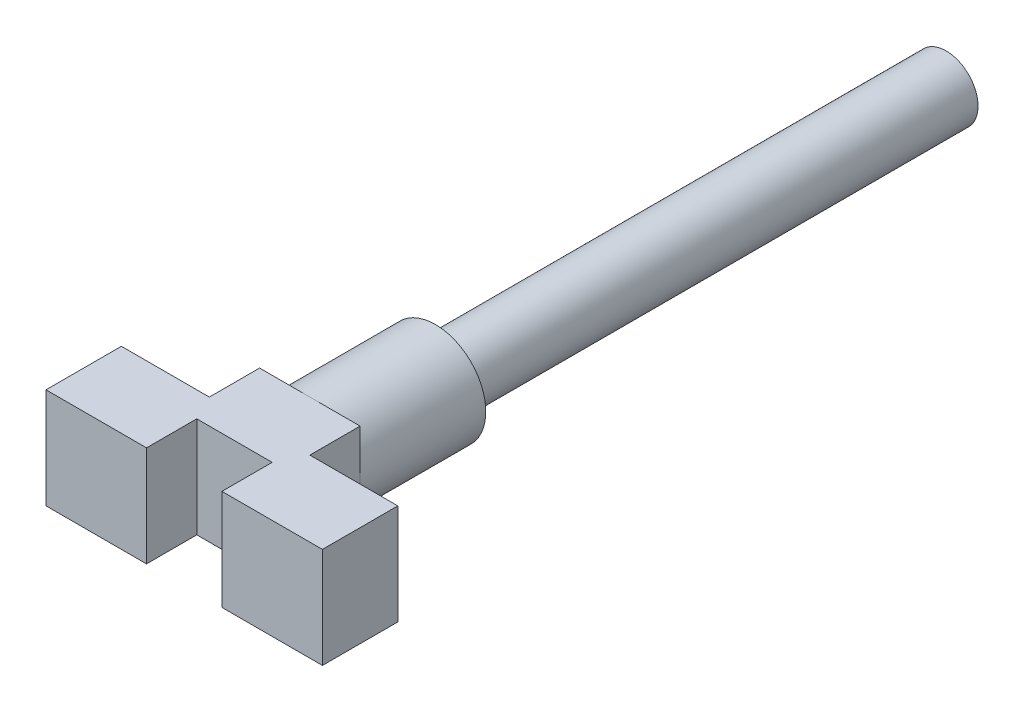
SolidWorks part; units mm, degrees
ref_plane "Front Plane" through (0, 0, 0) normal (0, 0, 1) x (1, 0, 0)
ref_plane "Top Plane" through (0, 0, 0) normal (0, 1, 0) x (1, 0, 0)
ref_plane "Right Plane" through (0, 0, 0) normal (1, 0, 0) x (0, 0, -1)
sketch "Sketch1" plane through (0, 0, 0) normal (0, 1, 0) x (1, 0, 0)
  line L0 (5, 5) -> (-5, 5)
  line L1 (-5, 5) -> (-5, 0)
  line L2 (-5, 0) -> (-13.75, 0)
  line L3 (-13.75, 0) -> (-13.75, -7.5)
  line L4 (-13.75, -7.5) -> (-3.75, -7.5)
  line L5 (-3.75, -7.5) -> (-3.75, -2.5)
  line L6 (-3.75, -2.5) -> (3.75, -2.5)
  line L7 (3.75, -2.5) -> (3.75, -7.5)
  line L8 (3.75, -7.5) -> (13.75, -7.5)
  line L9 (13.75, -7.5) -> (13.75, 0)
  line L10 (13.75, 0) -> (5, 0)
  line L11 (5, 0) -> (5, 5)
  line L12 (0, -2.5) -> (0, 0) construction
  dimension "D1" = 10
  dimension "D2" = 10
  dimension "D3" = 2.5
  dimension "D4" = 5
  dimension "D5" = 5
  dimension "D6" = 7.5
extrude "Boss-Extrude1" add sketch "Sketch1" along normal mid plane 10
sketch "Sketch2" plane through (0, 0, -5) normal (0, 0, -1) x (-1, 0, 0)
  line L0 (-5, 5) -> (5, -5) construction
  circle A0 centre (0, 0) radius 5
  dimension "D1" = 10
extrude "Boss-Extrude2" add sketch "Sketch2" along normal blind 12.5
sketch "Sketch3" plane through (0, 0, -17.5) normal (0, 0, -1) x (-1, 0, 0)
  circle A0 centre (0, 0) radius 3.175
  dimension "D1" = 6.35
extrude "Boss-Extrude3" add sketch "Sketch3" along normal blind 50.8
